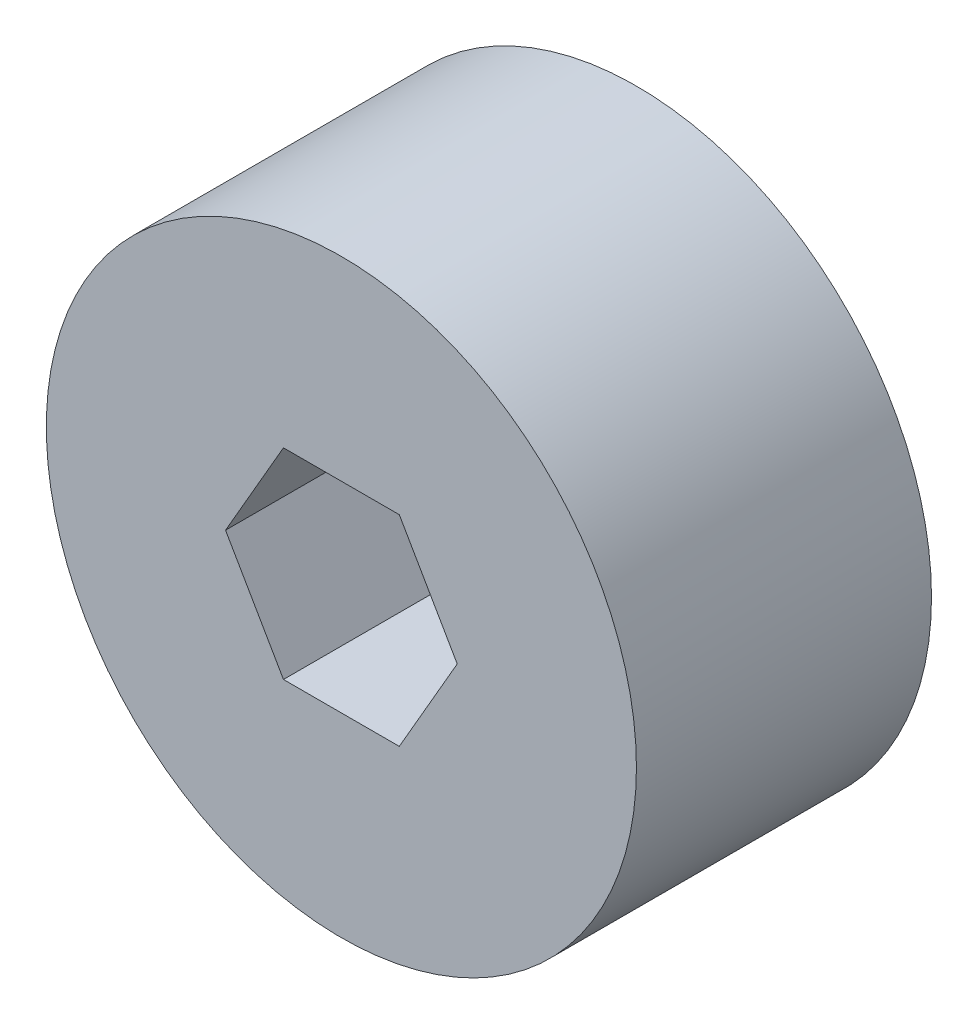
SolidWorks part; units mm, degrees
ref_plane "Front Plane" through (0, 0, 0) normal (1, 0, 0) x (0, 1, 0)
ref_plane "Top Plane" through (0, 0, 0) normal (0, 0, 1) x (0, 1, 0)
ref_plane "Right Plane" through (0, 0, 0) normal (0, 1, 0) x (-1, 0, 0)
sketch "Sketch2" plane through (0, 0, 0) normal (0, 0, 1) x (0, 1, 0)
  circle A0 centre (0, 0) radius 12.7
  dimension "D1" = 25.4
extrude "Boss-Extrude1" add sketch "Sketch2" along normal blind 12.7
sketch "Sketch3" plane through (0, 0, 12.7) normal (0, 0, 1) x (1, 0, 0)
  line L0 (-2.493, -4.318) -> (2.493, -4.318)
  line L1 (2.493, -4.318) -> (4.986, 0)
  line L2 (4.986, 0) -> (2.493, 4.318)
  line L3 (2.493, 4.318) -> (-2.493, 4.318)
  line L4 (-2.493, 4.318) -> (-4.986, 0)
  line L5 (-4.986, 0) -> (-2.493, -4.318)
  line L6 (0, -4.318) -> (0, 4.318) construction
  line L7 (-4.986, 0) -> (4.986, 0) construction
  point P8 (-0.8259, -0.7038)
  point P9 (-0.9838, 1.6086)
  point P11 (4.316, 0)
  dimension "D1" = 8.636
  dimension "D2" = 8.636
extrude "Cut-Extrude1" cut sketch "Sketch3" against normal through all
